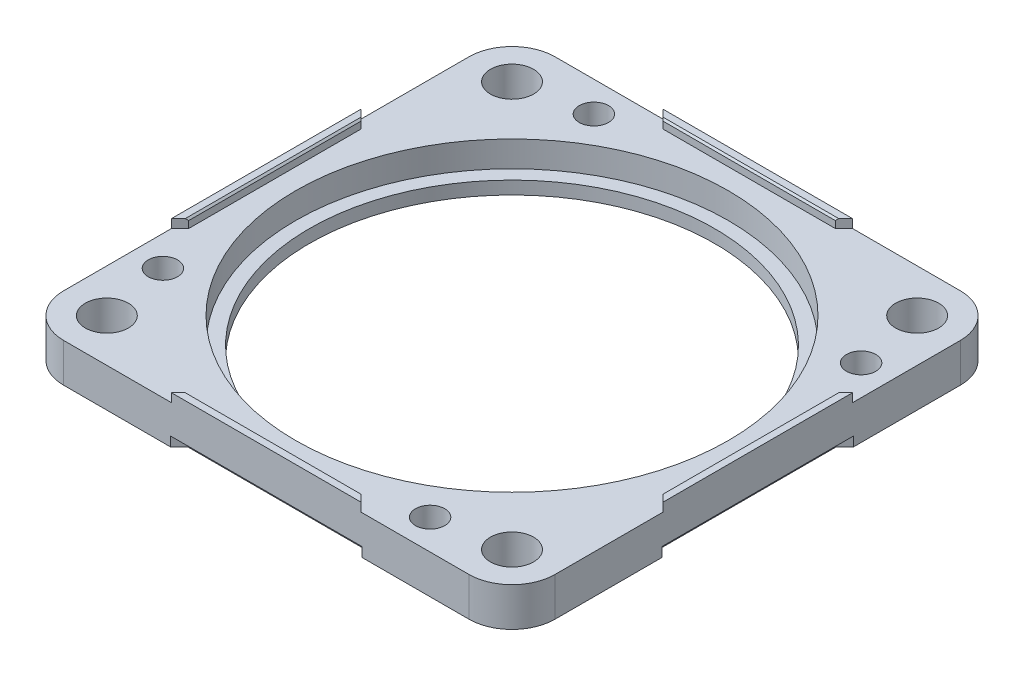
SolidWorks part; units mm, degrees
ref_plane "前视基准面" through (0, 0, 0) normal (0, 0, 1) x (1, 0, 0)
ref_plane "上视基准面" through (0, 0, 0) normal (0, 1, 0) x (1, 0, 0)
ref_plane "右视基准面" through (0, 0, 0) normal (1, 0, 0) x (0, 0, -1)
sketch "草图1" plane through (0, 0, 0) normal (0, 1, 0) x (1, 0, 0)
  line L1 (-28.5, -28.5) -> (28.5, -28.5)
  line L2 (-28.5, -28.5) -> (-28.5, 28.5)
  line L3 (-28.5, 28.5) -> (28.5, 28.5)
  line L4 (28.5, -28.5) -> (28.5, 28.5)
  line L5 (-28.5, -28.5) -> (28.5, 28.5) construction
  line L6 (-28.5, 28.5) -> (28.5, -28.5) construction
  point P0 (0, 0)
  dimension "D1" = 57
extrude "凸台-拉伸1" add sketch "草图1" along normal blind 4.5
fillet "圆角1" radius 5 4 edges at (-28.5, 2.25, -28.5) (-28.5, 2.25, 28.5) (28.5, 2.25, -28.5) (28.5, 2.25, 28.5)
sketch "草图2" plane through (0, 4.5, 0) normal (0, 1, 0) x (1, 0, 0)
  circle A0 centre (0, 0) radius 25.1
  dimension "D1" = 50.2
extrude "切除-拉伸1" cut sketch "草图2" against normal blind 3
sketch "草图3" plane through (0, 1.5, 0) normal (0, 1, 0) x (1, 0, 0)
  circle A0 centre (0, 0) radius 23.5
  dimension "D1" = 47
extrude "切除-拉伸2" cut sketch "草图3" against normal blind 1.5
sketch "草图4" plane through (0, 4.5, 0) normal (0, 1, 0) x (1, 0, 0)
  line L0 (-23.5, 23.5) -> (0, 0) construction
  line L1 (0, -0.7426) -> (0, -50000.7426) construction
  line L2 (23.5, 28.5) -> (-23.5, 28.5) construction
  circle A0 centre (-23.5, 23.5) radius 2.5
  circle A1 centre (-15.5, 25) radius 1.7
  dimension "D2" = 5
  dimension "D3" = 3.4
  dimension "D5" = 8
  dimension "D6" = 47
  dimension "D1" = 45
  dimension "D4" = 3.5
extrude "切除-拉伸3" cut sketch "草图4" against normal through all
sketch "草图5" plane through (0, 4.5, 0) normal (0, 1, 0) x (1, 0, 0)
  line L0 (-28.5, 11) -> (-28.5, -11)
  line L1 (-28.5, 23.5) -> (-28.5, -23.5) construction
  line L2 (-28.5, -11) -> (-27.5, -10)
  line L3 (-27.5, -10) -> (-27.5, 10)
  line L4 (-27.5, 10) -> (-28.5, 11)
  line L5 (-27.5, 0) -> (0, 0) construction
  dimension "D1" = 135
  dimension "D2" = 135
  dimension "D3" = 22
  dimension "D4" = 1
extrude "凸台-拉伸2" add sketch "草图5" along normal blind 1
chamfer "倒角1" distance 0.2 angle 45 1 edges at (-27.5, 5.5, 0)
sketch "草图6" plane through (0, 0, 0) normal (0, -1, 0) x (1, 0, 0)
  line L0 (-28.5, 11.1) -> (-28.5, -11.1)
  line L1 (-28.5, -23.5) -> (-28.5, 23.5) construction
  line L2 (-28.5, -11.1) -> (-27.5, -10.1)
  line L3 (-27.5, -10.1) -> (-27.5, 10.1)
  line L4 (-27.5, 10.1) -> (-28.5, 11.1)
  line L5 (-27.5, 0) -> (0, 0) construction
  dimension "D1" = 135
  dimension "D2" = 135
  dimension "D3" = 22.2
  dimension "D4" = 1
extrude "切除-拉伸4" cut sketch "草图6" against normal blind 1.1
pattern_circular "阵列(圆周)1" count 4 over 360 about axis through (0, 0, 0) along (0, 1, 0) of "切除-拉伸3", "凸台-拉伸2", "切除-拉伸4", "倒角1"
